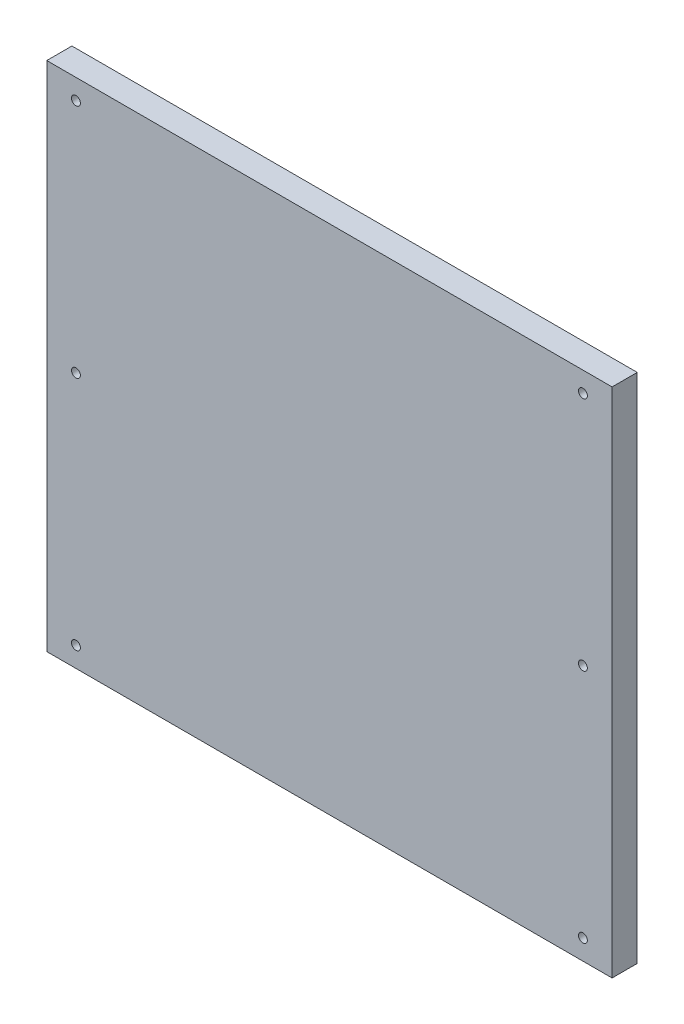
SolidWorks part; units mm, degrees
ref_plane "Front Plane" through (0, 0, 0) normal (0, 0, 1) x (1, 0, 0)
ref_plane "Top Plane" through (0, 0, 0) normal (0, 1, 0) x (1, 0, 0)
ref_plane "Right Plane" through (0, 0, 0) normal (1, 0, 0) x (0, 0, -1)
sketch "Sketch1" plane through (0, 0, 1063.625) normal (0, 0, 1) x (1, 0, 0)
  line L1 (214.1125, -146.25) -> (-214.1125, -146.25)
  line L2 (214.1125, -146.25) -> (214.1125, 241.5)
  line L3 (214.1125, 241.5) -> (-214.1125, 241.5)
  line L4 (-214.1125, -146.25) -> (-214.1125, 241.5)
extrude "Boss-Extrude1" add sketch "Sketch1" along normal blind 19.05
extrude "Cut-Extrude1" cut sketch "Sketch2" against normal through all
sketch "Sketch2" plane through (0, 0, 1061.72) normal (0, 0, -1) x (1, 0, 0)
  line L0 (189.0618, 136.1243) -> (194.9673, 125.8957) construction
  circle A0 centre (192.0145, 131.01) radius 3.3655
extrude "Cut-Extrude2" cut sketch "Sketch3" against normal through all
sketch "Sketch3" plane through (0, 0, 1061.72) normal (0, 0, -1) x (1, 0, 0)
  line L0 (197.92, -47.625) -> (186.109, -47.625) construction
  circle A0 centre (192.0145, -47.625) radius 3.3655
extrude "Cut-Extrude3" cut sketch "Sketch4" against normal blind 25.4
sketch "Sketch4" plane through (0, 0, 1061.72) normal (0, 0, -1) x (1, 0, 0)
  line L0 (194.9672, -231.3743) -> (189.0617, -221.1457) construction
  circle A0 centre (192.0145, -226.26) radius 3.3655
mirror "Mirror1" about plane through (0, 0, 0) normal (1, 0, 0) of "Cut-Extrude1", "Cut-Extrude2", "Cut-Extrude3"
sketch "Sketch5" plane through (0, 0, 1082.675) normal (0, 0, 1) x (1, 0, 0)
  circle A1 centre (192.0145, -131.01) radius 3.3655
  circle A2 centre (192.0145, -131.01) radius 3.3655
  circle A3 centre (-192.0145, 226.26) radius 3.3655
  circle A4 centre (-192.0145, 226.26) radius 3.3655
  circle A5 centre (-192.0145, 47.625) radius 3.3655
  circle A6 centre (-192.0145, 47.625) radius 3.3655
  circle A7 centre (-192.0145, -131.01) radius 3.3655
  circle A8 centre (-192.0145, -131.01) radius 3.3655
  circle A9 centre (192.0145, 226.26) radius 3.3655
  circle A10 centre (192.0145, 226.26) radius 3.3655
  circle A11 centre (192.0145, 47.625) radius 3.3655
  circle A12 centre (192.0145, 47.625) radius 3.3655
  dimension "D1" = 0
  dimension "D2" = 0
  dimension "D3" = 0
  dimension "D4" = 0
  dimension "D5" = 0
  dimension "D6" = 0
